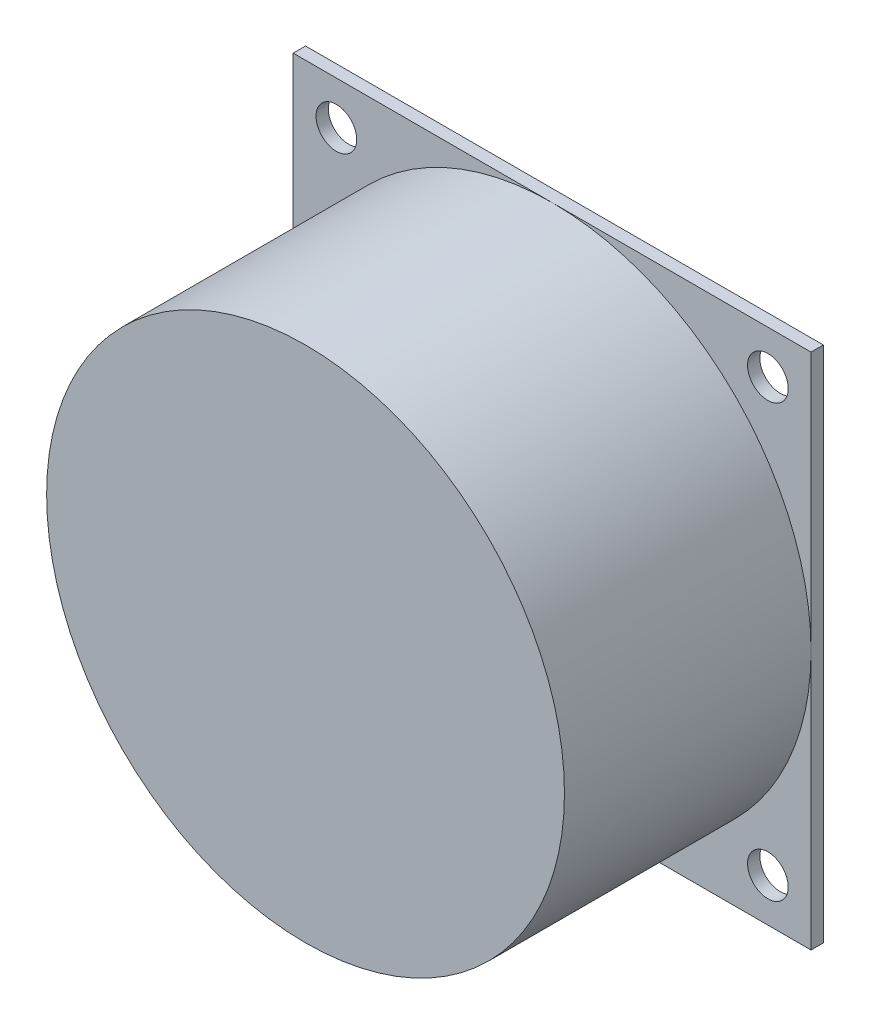
SolidWorks part; units mm, degrees
ref_plane "Plan de face" through (0, 0, 0) normal (0, 0, 1) x (1, 0, 0)
ref_plane "Plan de dessus" through (0, 0, 0) normal (0, 1, 0) x (1, 0, 0)
ref_plane "Plan de droite" through (0, 0, 0) normal (1, 0, 0) x (0, 0, -1)
sketch "Sketch1" plane through (0, 0, 0) normal (0, 0, 1) x (1, 0, 0)
  line L1 (17.5, -17.5) -> (-17.5, -17.5) construction
  line L2 (17.5, -17.5) -> (17.5, 17.5) construction
  line L3 (17.5, 17.5) -> (-17.5, 17.5) construction
  line L4 (-17.5, -17.5) -> (-17.5, 17.5) construction
  line L5 (17.5, -17.5) -> (-17.5, 17.5) construction
  line L6 (17.5, 17.5) -> (-17.5, -17.5) construction
  line L7 (21, -21) -> (-21, -21)
  line L8 (21, -21) -> (21, 21)
  line L9 (21, 21) -> (-21, 21)
  line L10 (-21, -21) -> (-21, 21)
  line L11 (21, -21) -> (-21, 21) construction
  line L12 (21, 21) -> (-21, -21) construction
  circle A0 centre (-17.5, 17.5) radius 1.65
  circle A1 centre (17.5, 17.5) radius 1.65
  circle A2 centre (17.5, -17.5) radius 1.65
  circle A3 centre (-17.5, -17.5) radius 1.65
  point P0 (0, 0)
  point P10 (0, 0)
  dimension "D3" = 3.3
  dimension "D4" = 3.3
  dimension "D5" = 42
  dimension "D1" = 35
  dimension "D2" = 35
  dimension "D6" = 42
extrude "Boss-Extrude1" add sketch "Sketch1" along normal blind 1
sketch "Sketch2" plane through (0, 0, 1) normal (0, 0, 1) x (1, 0, 0)
  circle A0 centre (0, 0) radius 21
  dimension "D1" = 42
extrude "Boss-Extrude2" add sketch "Sketch2" along normal blind 20
sketch "Sketch3" plane through (0, 0, 0) normal (0, 0, -1) x (-1, 0, 0)
  circle A0 centre (0, 0) radius 5
  dimension "D1" = 10
extrude "Boss-Extrude3" add sketch "Sketch3" along normal blind 10
